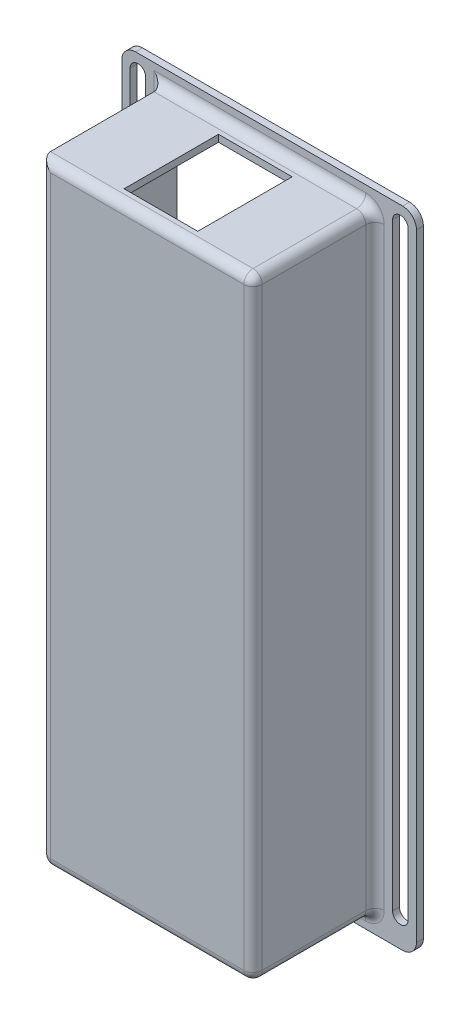
SolidWorks part; units mm, degrees
ref_plane "Front" through (0, 0, 0) normal (0, 0, 1) x (1, 0, 0)
ref_plane "Top" through (0, 0, 0) normal (0, 1, 0) x (1, 0, 0)
ref_plane "Right" through (0, 0, 0) normal (1, 0, 0) x (0, 0, -1)
sketch "Sketch1" plane through (0, 0, 0) normal (0, 0, 1) x (1, 0, 0)
  line L1 (-29, 70) -> (29, 70)
  line L2 (-32, 67) -> (-32, -67)
  line L3 (-29, -70) -> (29, -70)
  line L4 (32, 67) -> (32, -67)
  line L5 (-32, 70) -> (32, -70) construction
  line L6 (-32, -70) -> (32, 70) construction
  arc A0 (-29, -70) -> (-32, -67) centre (-29, -67) cw
  arc A1 (32, -67) -> (29, -70) centre (29, -67) cw
  arc A2 (29, 70) -> (32, 67) centre (29, 67) cw
  arc A3 (-29, 70) -> (-32, 67) centre (-29, 67) ccw
  point P0 (0, 0)
  dimension "D3" = 3
  dimension "D1" = 64
  dimension "D2" = 140
extrude "Boss-Extrude1" add sketch "Sketch1" along normal blind 1.5
sketch "Sketch2" plane through (0, 0, 1.5) normal (0, 0, 1) x (1, 0, 0)
  line L1 (-23, 66.5) -> (23, 66.5)
  line L2 (-23, 66.5) -> (-23, -66.5)
  line L3 (-23, -66.5) -> (23, -66.5)
  line L4 (23, 66.5) -> (23, -66.5)
  line L5 (-23, 66.5) -> (23, -66.5) construction
  line L6 (-23, -66.5) -> (23, 66.5) construction
  point P0 (0, 0)
  dimension "D1" = 46
  dimension "D2" = 133
extrude "Boss-Extrude2" add sketch "Sketch2" along normal blind 26.5
sketch "Sketch3" plane through (0, 0, 0) normal (0, 0, -1) x (-1, 0, 0)
  line L0 (-21.5, 65) -> (-21.5, -65)
  line L1 (-21.5, -65) -> (21.5, -65)
  line L2 (21.5, -65) -> (21.5, 65)
  line L3 (21.5, 65) -> (-21.5, 65)
  line L4 (-23, 66.5) -> (-23, -66.5)
  line L5 (23, 66.5) -> (-23, 66.5)
  line L6 (23, -66.5) -> (23, 66.5)
  line L7 (-23, -66.5) -> (23, -66.5)
  line L8 (-23, 66.5) -> (-23, -66.5)
  line L9 (23, 66.5) -> (-23, 66.5)
  line L10 (23, -66.5) -> (23, 66.5)
  line L11 (-23, -66.5) -> (23, -66.5)
  dimension "D1" = 0
  dimension "D2" = 1.5
extrude "Cut-Extrude1" cut sketch "Sketch3" against normal offset from surface (26.5 mm away) 1.5 contours L0 L1 L2 L3 up to face at (0, 0, 28)
sketch "Sketch4" plane through (0, 0, 0) normal (0, 0, -1) x (-1, 0, 0)
  line L0 (-30.2, 66.33) -> (-30.2, -63.67)
  line L1 (-26.8, 66.33) -> (-26.8, -63.67)
  line L2 (-28.5, 68.03) -> (-28.5, -65.37) construction
  line L3 (0, 0) -> (0, 50000) construction
  line L4 (30.2, 66.33) -> (30.2, -63.67)
  line L5 (26.8, 66.33) -> (26.8, -63.67)
  arc A0 (-30.2, -63.67) -> (-26.8, -63.67) centre (-28.5, -63.67) ccw
  arc A1 (-30.2, 66.33) -> (-26.8, 66.33) centre (-28.5, 66.33) cw
  arc A2 (30.2, -63.67) -> (26.8, -63.67) centre (28.5, -63.67) cw
  arc A3 (30.2, 66.33) -> (26.8, 66.33) centre (28.5, 66.33) ccw
  dimension "D1" = 3.4
  dimension "D2" = 130
  dimension "D3" = 28.5
extrude "Cut-Extrude2" cut sketch "Sketch4" against normal blind 1.5
sketch "Sketch5" plane through (0, 66.5, 0) normal (0, 1, 0) x (1, 0, 0)
  line L0 (-23, -28) -> (-23, -1.5) construction
  line L1 (-8, -4.5) -> (8, -4.5)
  line L2 (-8, -4.5) -> (-8, -25)
  line L3 (-8, -25) -> (8, -25)
  line L4 (8, -4.5) -> (8, -25)
  line L5 (-8, -4.5) -> (8, -25) construction
  line L6 (-8, -25) -> (8, -4.5) construction
  line L7 (23, -1.5) -> (-23, -1.5) construction
  point P0 (0, -14.75)
  point P7 (-23, -14.75)
  dimension "D1" = 15
  dimension "D2" = 3
extrude "Cut-Extrude3" cut sketch "Sketch5" against normal blind 1.5
fillet "Fillet1" radius 2 11 edges at (-23, 0, 1.5) (0, -66.5, 1.5) (0, 66.5, 1.5) (23, 0, 1.5) (23, 66.5, 14.75) (23, -66.5, 14.75) (-23, -66.5, 14.75) (0, -66.5, 28) (-23, 0, 28) (0, 66.5, 28) (23, 0, 28)
